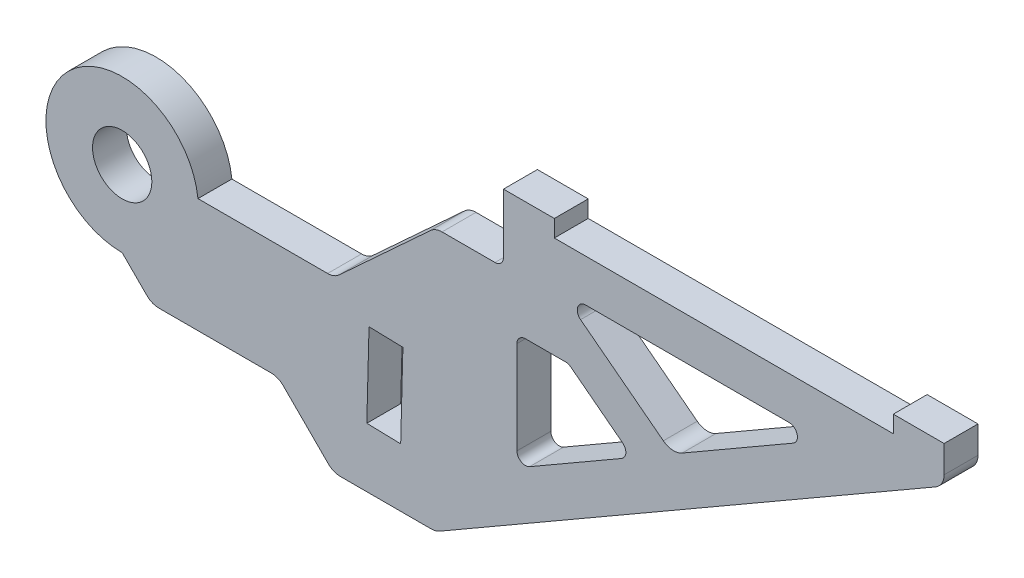
SolidWorks part; units mm, degrees
ref_plane "Front Plane" through (0, 0, 0) normal (0, 0, 1) x (1, 0, 0)
ref_plane "Top Plane" through (0, 0, 0) normal (0, 1, 0) x (1, 0, 0)
ref_plane "Right Plane" through (0, 0, 0) normal (1, 0, 0) x (0, 0, -1)
sketch "Sketch1" plane through (0, 0, 0) normal (0, 0, 1) x (1, 0, 0)
  line L0 (4.4721, 0.5) -> (12.1232, 0.5)
  line L1 (12.8005, 0.7644) -> (18.1995, 5.7356)
  line L2 (18.8768, 6) -> (22, 6)
  line L3 (0, -4.5) -> (1.4576, -5.9576)
  line L4 (9.5008, -6.5433) -> (12.1646, -9.2071)
  line L5 (12.8717, -9.5) -> (18.233, -9.5)
  line L6 (18.733, -9.366) -> (25.7239, -5.3298)
  line L7 (0, 0) -> (0, 13.2061) construction
  line L8 (12.5134, 0.5) -> (16.9058, 0.5) construction
  line L9 (9.2079, -6.2504) -> (31.4975, -6.2504) construction
  line L10 (0, -4.5) -> (5.876, -4.5) construction
  line L11 (2.1647, -6.2504) -> (8.7937, -6.2504)
  line L12 (27.8019, 6.5) -> (39.3477, 6.5)
  line L13 (39.5977, 5.567) -> (33.0414, 1.7817)
  line L14 (31.9326, 1.8545) -> (27.048, 5.6034)
  line L15 (27.3524, 6.5) -> (27.8019, 6.5)
  line L16 (29.5258, 0.5502) -> (26.4685, 2.8966)
  line L17 (26.1641, 3) -> (23.7939, 3)
  line L18 (23.2939, 2.5) -> (23.2939, -2.98)
  line L19 (24.0439, -3.413) -> (29.4714, -0.2795)
  line L20 (16.4339, -6.0515) -> (18.5009, -9.5) construction
  line L21 (14.4346, -5.9991) -> (12.4575, -9.5) construction
  line L22 (14.5654, -1.0009) -> (14.4346, -5.9991)
  line L23 (14.5, -3.5) -> (16.4993, -3.5524) construction
  line L24 (14.5, -3.5) -> (14.5, -10.4424) construction
  line L30 (22.5, 6.5) -> (22.5, 10)
  line L31 (22.5, 10) -> (25.5, 10)
  line L32 (25.5, 10) -> (25.5, 9)
  line L33 (25.5, 9) -> (45.5, 9)
  line L34 (45.5, 9) -> (45.5, 10)
  line L35 (45.5, 10) -> (48.5, 10)
  line L36 (48.5, 10) -> (48.5, 8.3973)
  line L37 (48, 7.5313) -> (25.7239, -5.3298)
  line L39 (0, 0) -> (39.584, 0) construction
  line L41 (14.5654, -1.0009) -> (16.5648, -1.0532)
  line L43 (14.4346, -5.9991) -> (16.4339, -6.0515)
  line L44 (16.5648, -1.0532) -> (16.4339, -6.0515)
  arc A0 (39.3477, 6.5) -> (39.5977, 5.567) centre (39.3477, 6) cw
  arc A1 (27.048, 5.6034) -> (27.3524, 6.5) centre (27.3524, 6) cw
  arc A2 (33.0414, 1.7817) -> (31.9326, 1.8545) centre (32.5414, 2.6477) cw
  arc A3 (26.4685, 2.8966) -> (26.1641, 3) centre (26.1641, 2.5) ccw
  arc A4 (23.7939, 3) -> (23.2939, 2.5) centre (23.7939, 2.5) ccw
  arc A5 (23.2939, -2.98) -> (24.0439, -3.413) centre (23.7939, -2.98) ccw
  arc A6 (29.5258, 0.5502) -> (29.4714, -0.2795) centre (29.2214, 0.1536) cw
  arc A7 (48.5, 8.3973) -> (48, 7.5313) centre (47.5, 8.3973) cw
  arc A8 (12.1232, 0.5) -> (12.8005, 0.7644) centre (12.1232, 1.5) ccw
  circle A9 centre (0, 0) radius 1.75
  arc A10 (4.4721, 0.5) -> (0, -4.5) centre (0, 0) ccw
  arc A11 (18.1995, 5.7356) -> (18.8768, 6) centre (18.8768, 5) cw
  arc A12 (18.233, -9.5) -> (18.733, -9.366) centre (18.233, -8.5) ccw
  arc A13 (12.1646, -9.2071) -> (12.8717, -9.5) centre (12.8717, -8.5) ccw
  arc A14 (8.7937, -6.2504) -> (9.5008, -6.5433) centre (8.7937, -7.2504) cw
  arc A15 (1.4576, -5.9576) -> (2.1647, -6.2504) centre (2.1647, -5.2504) ccw
  arc A16 (22, 6) -> (22.5, 6.5) centre (22, 6.5) ccw
  point P34 (14.5, -3.5)
  dimension "D1" = 3.5
  dimension "D2" = 9
  dimension "D21" = 0.5
  dimension "D22" = 1
  dimension "D23" = 0.5
  dimension "D27" = 1
  dimension "D28" = 0.5
  dimension "D3" = 5
  dimension "D4" = 2
  dimension "D5" = 14.5
  dimension "D6" = 3.5
  dimension "D7" = 1.5
  dimension "D8" = 3
  dimension "D9" = 30
  dimension "D10" = 1
  dimension "D11" = 1
  dimension "D12" = 22.5
  dimension "D13" = 45
  dimension "D14" = 45
  dimension "D15" = 0.5
  dimension "D16" = 2.5
  dimension "D17" = 2.5
  dimension "D18" = 2.5
  dimension "D19" = 2.5
  dimension "D20" = 3
  dimension "D24" = 20
  dimension "D25" = 9
  dimension "D26" = 6
extrude "Boss-Extrude1" add sketch "Sketch1" along normal blind 2
